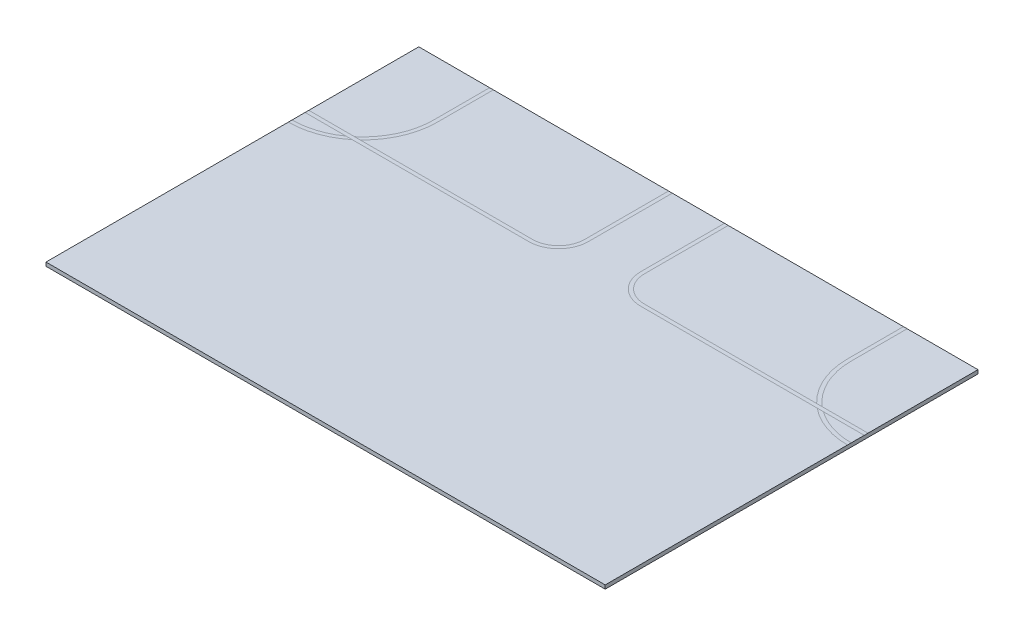
SolidWorks part; units mm, degrees
ref_plane "Plan de face" through (0, 0, 0) normal (0, 0, 1) x (1, 0, 0)
ref_plane "Plan de dessus" through (0, 0, 0) normal (0, 1, 0) x (1, 0, 0)
ref_plane "Plan de droite" through (0, 0, 0) normal (1, 0, 0) x (0, 0, -1)
sketch "Esquisse1" plane through (0, 0, 0) normal (0, 1, 0) x (1, 0, 0)
  line L1 (2866.5655, -1917.9541) -> (-133.4345, -1917.9541)
  line L2 (2866.5655, -1917.9541) -> (2866.5655, 82.0459)
  line L3 (2866.5655, 82.0459) -> (-133.4345, 82.0459)
  line L4 (-133.4345, -1917.9541) -> (-133.4345, 82.0459)
  dimension "D1" = 3000
  dimension "D2" = 2000
extrude "Boss.-Extru.1" add sketch "Esquisse1" along normal blind 20
sketch "Esquisse2" plane through (0, 20, 0) normal (0, 1, 0) x (1, 0, 0)
  line L0 (-133.4345, 82.0459) -> (-133.4345, -1917.9541) construction
  line L1 (-133.4345, 82.0459) -> (266.5655, 82.0459)
  line L2 (-133.4345, 82.0459) -> (-133.4345, -217.9541)
  line L3 (-133.4345, -217.9541) -> (266.5655, -217.9541)
  line L4 (266.5655, 82.0459) -> (266.5655, -217.9541)
  line L5 (2866.5655, 82.0459) -> (2466.5655, 82.0459)
  line L6 (2866.5655, 82.0459) -> (2866.5655, -217.9541)
  line L7 (2866.5655, -217.9541) -> (2466.5655, -217.9541)
  line L8 (2466.5655, 82.0459) -> (2466.5655, -217.9541)
  line L9 (2866.5655, -1917.9541) -> (2866.5655, 82.0459) construction
  line L10 (-133.4345, -217.9541) -> (-133.4345, -617.9541)
  line L11 (2866.5655, -217.9541) -> (2866.5655, -617.9541)
  arc A0 (266.5655, -217.9541) -> (-133.4345, -617.9541) centre (-133.4345, -217.9541) cw
  arc A1 (2466.5655, -217.9541) -> (2866.5655, -617.9541) centre (2866.5655, -217.9541) ccw
  line M1 (2866.5655, -1917.9541) -> (2866.5655, 82.0459)
  line M2 (2866.5655, 82.0459) -> (-133.4345, 82.0459)
  line M3 (-133.4345, 82.0459) -> (-133.4345, -1917.9541)
  line M4 (-133.4345, -1917.9541) -> (2866.5655, -1917.9541)
  dimension "D1" = 400
  dimension "D3" = 400
  dimension "D2" = 300
  dimension "D4" = 300
extrude "Boss.-Extru.2" add sketch "Esquisse2" along normal blind 0.0001 contours A1 L8 L4 A0 M2 M3 M4 M1
sketch "Esquisse5" plane through (0, 20, 0) normal (0, 1, 0) x (1, 0, 0)
  line L0 (-133.4345, 82.0459) -> (-133.4345, -617.9541) construction
  line L1 (-133.4345, 82.0459) -> (246.5655, 82.0459)
  line L2 (-133.4345, 82.0459) -> (-133.4345, -217.9541)
  line L3 (-133.4345, -217.9541) -> (246.5655, -217.9541)
  line L4 (246.5655, 82.0459) -> (246.5655, -217.9541)
  line L5 (-133.4345, -217.9541) -> (-133.4345, -597.9541)
  line L6 (1366.5655, 82.0459) -> (1366.5655, -1917.9541) construction
  line L7 (2466.5655, 82.0459) -> (266.5655, 82.0459) construction
  line L8 (-133.4345, -1917.9541) -> (2866.5655, -1917.9541) construction
  line L9 (2866.5655, -217.9541) -> (2866.5655, -597.9541)
  line L10 (2866.5655, 82.0459) -> (2486.5655, 82.0459)
  line L11 (2866.5655, 82.0459) -> (2866.5655, -217.9541)
  line L12 (2866.5655, -217.9541) -> (2486.5655, -217.9541)
  line L13 (2486.5655, 82.0459) -> (2486.5655, -217.9541)
  line L14 (246.5655, 82.0459) -> (266.5655, 82.0459)
  line L15 (266.5655, 82.0459) -> (266.5655, -217.9541)
  line L16 (-133.4345, -617.9541) -> (-133.4345, -597.9541)
  line L17 (2486.5655, 82.0459) -> (2466.5655, 82.0459)
  line L18 (2466.5655, 82.0459) -> (2466.5655, -217.9541)
  line L19 (2866.5655, -597.9541) -> (2866.5655, -617.9541)
  arc A0 (246.5655, -217.9541) -> (-133.4345, -597.9541) centre (-133.4345, -217.9541) cw
  arc A1 (2486.5655, -217.9541) -> (2866.5655, -597.9541) centre (2866.5655, -217.9541) ccw
  arc A2 (266.5655, -217.9541) -> (-133.4345, -617.9541) centre (-133.4345, -217.9541) cw
  arc A3 (-133.4345, -617.9541) -> (266.5655, -217.9541) centre (-133.4345, -217.9541) ccw construction
  arc A4 (2866.5655, -617.9541) -> (2466.5655, -217.9541) centre (2866.5655, -217.9541) cw
  arc A5 (2466.5655, -217.9541) -> (2866.5655, -617.9541) centre (2866.5655, -217.9541) ccw construction
  arc M1 (-133.4345, -617.9541) -> (266.5655, -217.9541) centre (-133.4345, -217.9541) ccw
  line M2 (266.5655, -217.9541) -> (266.5655, 82.0459)
  line M3 (266.5655, 82.0459) -> (-133.4345, 82.0459)
  line M4 (-133.4345, 82.0459) -> (-133.4345, -617.9541)
  dimension "D1" = 380
  dimension "D2" = 300
extrude "Boss.-Extru.6" add sketch "Esquisse5" along normal blind 0.0002 contours L4 A0 M4 M1 M2 M3
sketch "Esquisse6" plane through (0, 20, 0) normal (0, 1, 0) x (1, 0, 0)
  line L0 (2866.5655, -1917.9541) -> (2866.5655, -617.9541) construction
  line L1 (2466.5655, 82.0459) -> (2486.5655, 82.0459)
  line L2 (2466.5655, 82.0459) -> (2466.5655, -217.9541)
  line L3 (2466.5655, -217.9541) -> (2486.5655, -217.9541)
  line L4 (2486.5655, 82.0459) -> (2486.5655, -217.9541)
  line L5 (2866.5655, -617.9541) -> (2866.5655, 82.0459) construction
  line L6 (2866.5655, -617.9541) -> (2866.5655, -597.9541)
  arc A0 (2466.5655, -217.9541) -> (2866.5655, -617.9541) centre (2866.5655, -217.9541) ccw
  arc A1 (2486.5655, -217.9541) -> (2866.5655, -597.9541) centre (2866.5655, -217.9541) ccw
  line M1 (2466.5655, 82.0459) -> (2466.5655, -217.9541)
  arc M2 (2466.5655, -217.9541) -> (2866.5655, -617.9541) centre (2866.5655, -217.9541) ccw
  line M3 (2866.5655, -617.9541) -> (2866.5655, 82.0459)
  line M4 (2866.5655, 82.0459) -> (2466.5655, 82.0459)
  dimension "D1" = 380
  dimension "D2" = 300
extrude "Boss.-Extru.8" add sketch "Esquisse6" along normal blind 0.0002 contours A1 L3 M2 M3 | L4 L3 M4 M1
sketch "Esquisse7" plane through (0, 20, 0) normal (0, 1, 0) x (1, 0, 0)
  line L0 (-133.4345, 82.0459) -> (-133.4345, -597.9541) construction
  line L1 (-133.4345, -507.9541) -> (1066.5655, -507.9541)
  line L2 (-133.4345, -507.9541) -> (-133.4345, -527.9541)
  line L3 (-133.4345, -527.9541) -> (1066.5655, -527.9541)
  line L4 (1066.5655, -507.9541) -> (1066.5655, -527.9541)
  line L5 (2466.5655, 82.0459) -> (266.5655, 82.0459) construction
  line L6 (1206.5655, 82.0459) -> (1226.5655, 82.0459)
  line L7 (1206.5655, 82.0459) -> (1206.5655, -367.9541)
  line L8 (1206.5655, -367.9541) -> (1226.5655, -367.9541)
  line L9 (1226.5655, 82.0459) -> (1226.5655, -367.9541)
  line L10 (1366.5655, 82.0459) -> (1366.5655, -1917.9541) construction
  line L11 (-133.4345, -1917.9541) -> (2866.5655, -1917.9541) construction
  line L12 (1526.5655, -367.9541) -> (1506.5655, -367.9541)
  line L13 (1666.5655, -507.9541) -> (1666.5655, -527.9541)
  line L14 (2866.5655, -507.9541) -> (2866.5655, -527.9541)
  line L15 (1526.5655, 82.0459) -> (1506.5655, 82.0459)
  line L16 (2866.5655, -507.9541) -> (1666.5655, -507.9541)
  line L17 (2866.5655, -527.9541) -> (1666.5655, -527.9541)
  line L18 (1506.5655, 82.0459) -> (1506.5655, -367.9541)
  line L19 (1526.5655, 82.0459) -> (1526.5655, -367.9541)
  arc A0 (1206.5655, -367.9541) -> (1066.5655, -507.9541) centre (1066.5655, -367.9541) cw
  arc A1 (1226.5655, -367.9541) -> (1066.5655, -527.9541) centre (1066.5655, -367.9541) cw
  arc A2 (1506.5655, -367.9541) -> (1666.5655, -527.9541) centre (1666.5655, -367.9541) ccw
  arc A3 (1526.5655, -367.9541) -> (1666.5655, -507.9541) centre (1666.5655, -367.9541) ccw
  arc M1 (-133.4345, -597.9541) -> (246.5655, -217.9541) centre (-133.4345, -217.9541) ccw
  line M4 (-133.4345, 82.0459) -> (-133.4345, -597.9541)
  dimension "D1" = 20
  dimension "D2" = 20
  dimension "D3" = 1200
  dimension "D4" = 450
  dimension "D5" = 1340
  dimension "D6" = 590
extrude "Boss.-Extru.9" add sketch "Esquisse7" along normal blind 0.0003 contours L9 L6 L7 L8 | L19 L15 L18 L12 | A3 L12 A2 L13 | A1 L8 A0 L4 | L4 L1 L3 M1 | L17 L14 L16 L13 | L3 L1 M4 M1
